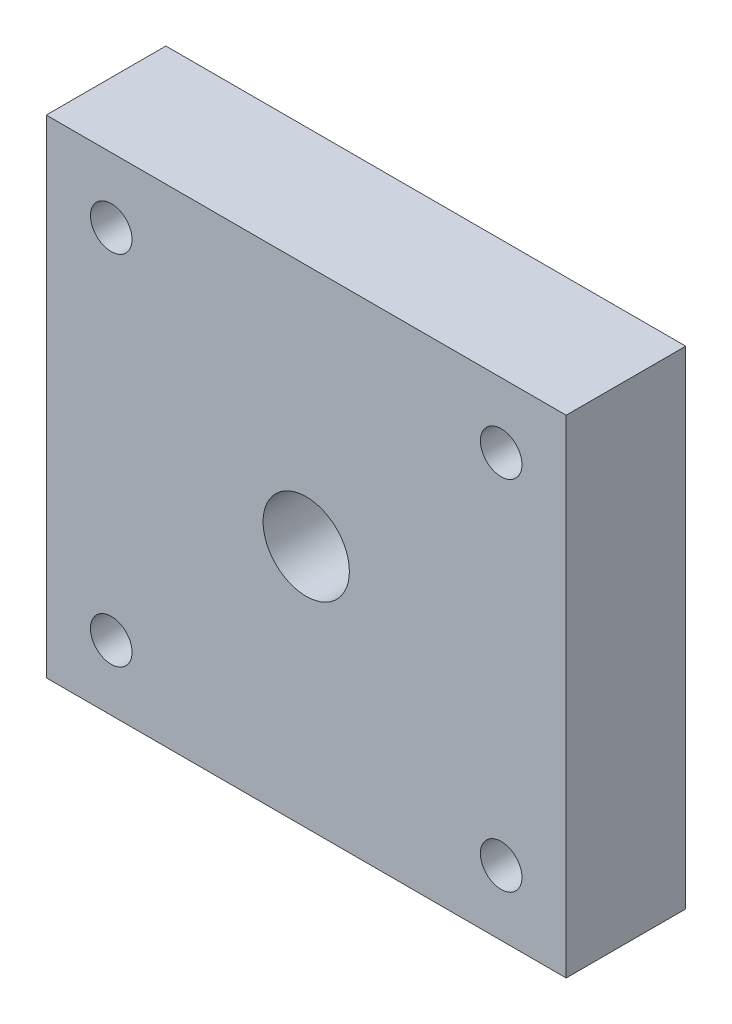
SolidWorks part; units mm, degrees
ref_plane "Front Plane" through (0, 0, 0) normal (0, 0, 1) x (1, 0, 0)
ref_plane "Top Plane" through (0, 0, 0) normal (0, 1, 0) x (1, 0, 0)
ref_plane "Right Plane" through (0, 0, 0) normal (1, 0, 0) x (0, 0, -1)
sketch "Sketch1" plane through (0, 0, 0) normal (0, 0, 1) x (1, 0, 0)
  line L1 (0, 0) -> (50.8, 0)
  line L2 (0, 0) -> (0, 47.625)
  line L3 (0, 47.625) -> (50.8, 47.625)
  line L4 (50.8, 0) -> (50.8, 47.625)
  dimension "D1" = 50.8
  dimension "D2" = 47.625
extrude "Boss-Extrude1" add sketch "Sketch1" along normal blind 11.684
sketch "Sketch2" plane through (0, 0, 11.684) normal (0, 0, 1) x (1, 0, 0)
  line L0 (50.8, 0) -> (50.8, 47.625) construction
  line L1 (50.8, 47.625) -> (0, 47.625) construction
  circle A0 centre (25.4, 23.8125) radius 4.2164
  dimension "D1" = 8.4328
  dimension "D2" = 25.4
  dimension "D3" = 23.8125
extrude "Cut-Extrude1" cut sketch "Sketch2" against normal through all
sketch "Sketch3" plane through (0, 0, 11.684) normal (0, 0, 1) x (1, 0, 0)
  line L0 (0, 47.625) -> (0, 0) construction
  line L1 (50.8, 47.625) -> (0, 47.625) construction
  line L2 (50.8, 0) -> (50.8, 47.625) construction
  line L3 (0, 0) -> (50.8, 0) construction
  circle A0 centre (6.35, 41.275) radius 2.032
  circle A1 centre (44.45, 41.275) radius 2.032
  circle A2 centre (44.45, 6.35) radius 2.032
  circle A3 centre (6.35, 6.35) radius 2.032
  dimension "D1" = 4.064
  dimension "D2" = 4.064
  dimension "D3" = 4.064
  dimension "D4" = 4.064
  dimension "D5" = 6.35
  dimension "D6" = 6.35
  dimension "D7" = 6.35
  dimension "D8" = 6.35
  dimension "D9" = 6.35
  dimension "D10" = 6.35
  dimension "D11" = 6.35
  dimension "D12" = 6.35
extrude "Cut-Extrude2" cut sketch "Sketch3" against normal through all
